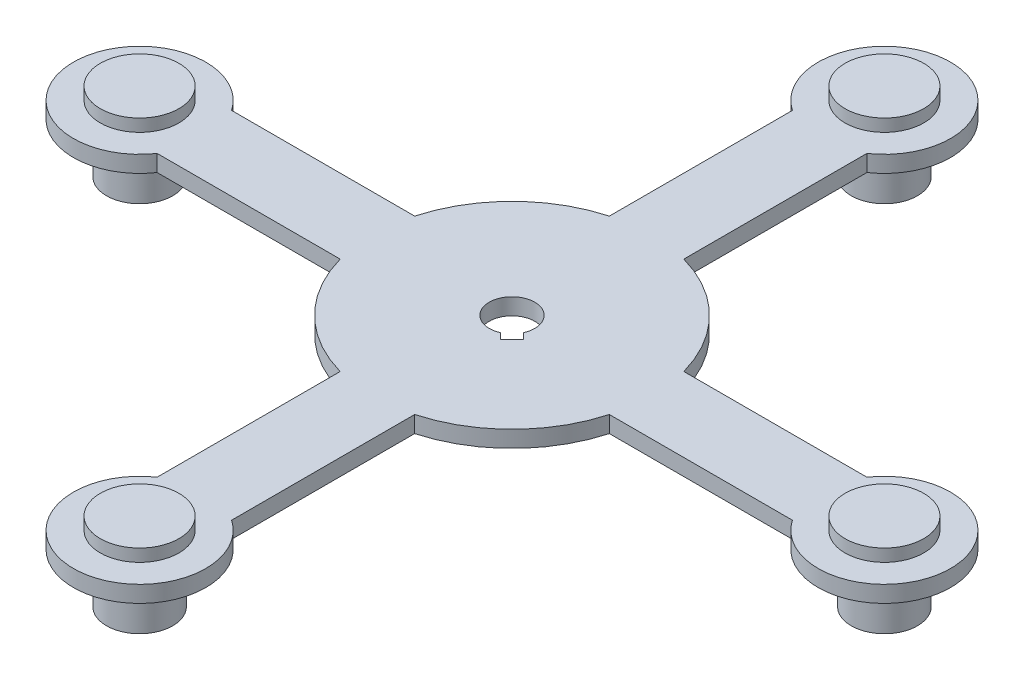
SolidWorks part; units mm, degrees
ref_plane "Front Plane" through (0, 0, 0) normal (0, 0, 1) x (1, 0, 0)
ref_plane "Top Plane" through (0, 0, 0) normal (0, 1, 0) x (1, 0, 0)
ref_plane "Right Plane" through (0, 0, 0) normal (1, 0, 0) x (0, 0, -1)
sketch "Sketch1" plane through (0, 0, 0) normal (0, 1, 0) x (1, 0, 0)
  line L1 (-18, -180) -> (18, -180)
  line L2 (-18, -180) -> (-18, 180)
  line L3 (-18, 180) -> (18, 180)
  line L4 (18, -180) -> (18, 180)
  line L5 (-18, -180) -> (18, 180) construction
  line L6 (-18, 180) -> (18, -180) construction
  line L7 (-180, -18) -> (180, -18)
  line L8 (-180, -18) -> (-180, 18)
  line L9 (-180, 18) -> (180, 18)
  line L10 (180, -18) -> (180, 18)
  line L11 (-180, -18) -> (180, 18) construction
  line L12 (-180, 18) -> (180, -18) construction
  circle A0 centre (0, 180) radius 32
  circle A1 centre (180, 0) radius 32
  circle A2 centre (0, -180) radius 32
  circle A3 centre (-180, 0) radius 32
  circle A4 centre (0, 0) radius 67.5
  point P0 (0, 0)
  point P5 (0, 0)
  dimension "D3" = 64
  dimension "D4" = 135
  dimension "D1" = 360
  dimension "D2" = 36
extrude "Boss-Extrude1" add sketch "Sketch1" along normal mid plane 8 contours L9 A3 L7 L8 | A3 L7 L2 L9 | L7 A3 L9 L8 | A0 L2 L9 L4 | A2 L4 L7 L2 | L9 L2 L7 L4 | A1 L9 L4 L7 | L4 A0 L2 L3 | L2 A0 L4 L3 | L7 A1 L9 L10 | L9 A1 L7 L10 | L2 A2 L4 L1 | L4 A2 L2 L1 | L7 A4 L2 | L9 A4 L7 L2 | L2 A4 L9 | L4 A4 L2 L9 | L9 A4 L4 | L4 A4 L7 | L2 A4 L4 L7 | L7 A4 L9 L4
sketch "Sketch2" plane through (0, -4, 0) normal (0, 1, 0) x (1, 0, 0)
  circle A0 centre (-180, 0) radius 16
  circle A1 centre (0, -180) radius 16
  circle A2 centre (180, 0) radius 16
  circle A3 centre (0, 180) radius 16
  dimension "D1" = 32
extrude "Boss-Extrude2" add sketch "Sketch2" against normal blind 24
sketch "Sketch3" plane through (0, 4, 0) normal (0, 1, 0) x (1, 0, 0)
  circle A0 centre (-180, 0) radius 19
  circle A1 centre (0, 180) radius 19
  circle A2 centre (180, 0) radius 19
  circle A3 centre (0, -180) radius 19
  dimension "D1" = 38
extrude "Boss-Extrude3" add sketch "Sketch3" along normal blind 6
sketch "Sketch4" plane through (0, 4, 0) normal (0, 1, 0) x (1, 0, 0)
  line L0 (0, 0) -> (7.2457, -7.2457) construction
  line L1 (4.4173, -10.0741) -> (10.0741, -4.4173)
  line L2 (4.4173, -10.0741) -> (7.2832, -12.9401)
  line L3 (7.2832, -12.9401) -> (12.9401, -7.2832)
  line L4 (10.0741, -4.4173) -> (12.9401, -7.2832)
  line L5 (0, 0) -> (0, -11) construction
  circle A0 centre (0, 0) radius 11
  dimension "D1" = 22
  dimension "D2" = 8
  dimension "D3" = 14.3
  dimension "D4" = 45
extrude "Cut-Extrude1" cut sketch "Sketch4" against normal up to surface (8 mm away) contours L1 A0 | A0 L2 L3 L4 | L1 A0 up to face at (0, -4, -164)
